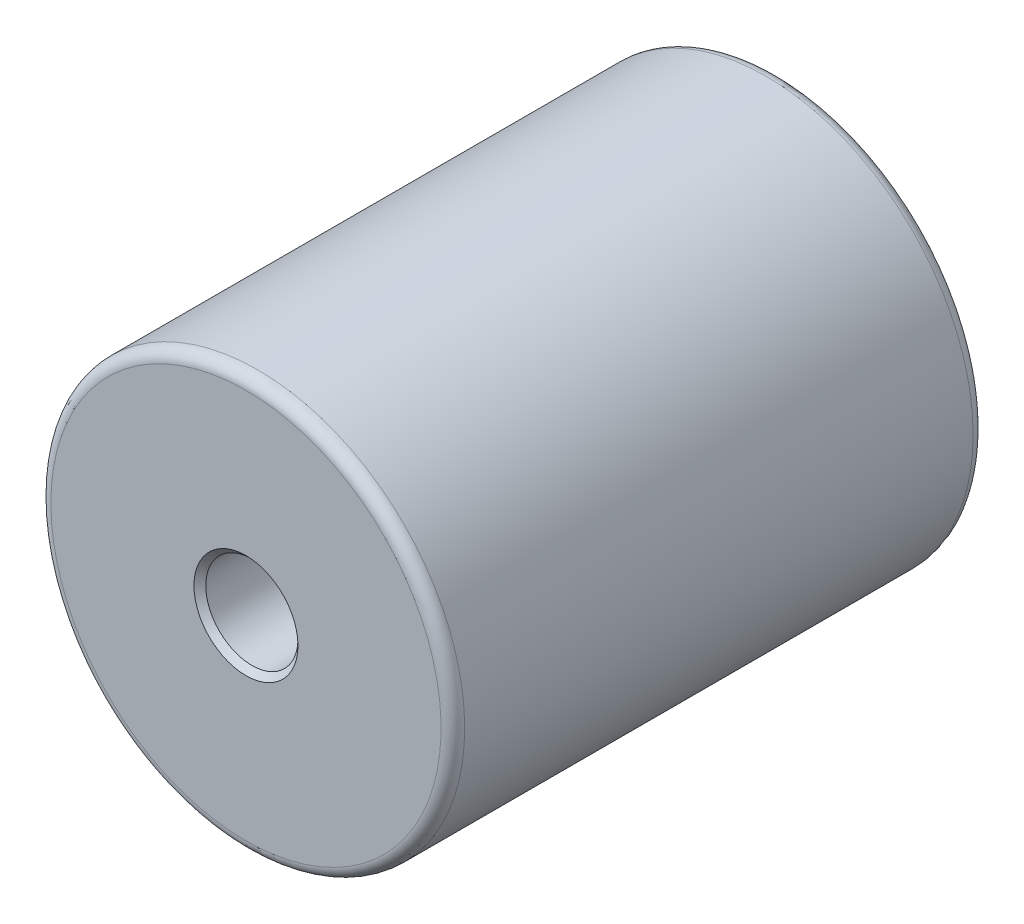
SolidWorks part; units mm, degrees
ref_plane "정면" through (0, 0, 0) normal (0, 0, 1) x (1, 0, 0)
ref_plane "윗면" through (0, 0, 0) normal (0, 1, 0) x (1, 0, 0)
ref_plane "우측면" through (0, 0, 0) normal (1, 0, 0) x (0, 0, -1)
sketch "스케치1" plane through (0, 0, 0) normal (0, 0, 1) x (1, 0, 0)
  line L0 (13.7295, 11.3315) -> (12.2791, 9.2601)
  line L1 (17.5559, 2.9486) -> (15.264, 1.8799)
  line L2 (15.2005, -1.8503) -> (17.4848, -2.9155)
  line L3 (14.0892, 5.9978) -> (16.6, 6.2175)
  line L4 (11.3315, -13.7295) -> (9.2601, -12.2791)
  line L5 (5.9978, -14.0892) -> (6.2175, -16.6)
  line L6 (12.2389, -9.2026) -> (13.6845, -11.2673)
  line L7 (16.6781, -6.2244) -> (14.159, -6.004)
  line L8 (-15.2005, 1.8503) -> (-17.4848, 2.9155)
  line L9 (-17.5559, -2.9486) -> (-15.264, -1.8799)
  line L10 (-16.6781, 6.2244) -> (-14.159, 6.004)
  line L11 (-12.2389, 9.2026) -> (-13.6845, 11.2673)
  line L12 (-14.0892, -5.9978) -> (-16.6, -6.2175)
  line L13 (-13.7295, -11.3315) -> (-12.2791, -9.2601)
  line L14 (-9.2026, -12.2389) -> (-11.2673, -13.6845)
  line L15 (-6.2244, -16.6781) -> (-6.004, -14.159)
  line L16 (-1.8503, -15.2005) -> (-2.9155, -17.4848)
  line L17 (2.9486, -17.5559) -> (1.8799, -15.264)
  line L18 (-5.9978, 14.0892) -> (-6.2175, 16.6)
  line L19 (-11.3315, 13.7295) -> (-9.2601, 12.2791)
  line L20 (9.2026, 12.2389) -> (11.2673, 13.6845)
  line L21 (6.2244, 16.6781) -> (6.004, 14.159)
  line L22 (1.8503, 15.2005) -> (2.9155, 17.4848)
  line L23 (-2.9486, 17.5559) -> (-1.8799, 15.264)
  line L24 (-21, 0) -> (21, 0) construction
  line L25 (0, -21) -> (0, 21) construction
  arc A0 (13.5918, 6.2861) -> (12.2786, 8.5724) centre (0, 0) ccw
  arc A1 (17.8195, -3.5773) -> (17.4848, -2.9155) centre (17.2312, -3.4593) ccw
  arc A2 (15.264, 1.8799) -> (14.9198, 1.2847) centre (15.5176, 1.3361) ccw
  arc A3 (17.5559, 2.9486) -> (17.8352, 3.498) centre (17.3446, 3.4018) ccw
  arc A4 (14.9138, -1.352) -> (15.2005, -1.8503) centre (15.4118, -1.3971) ccw
  arc A5 (14.9138, -1.352) -> (14.9198, 1.2847) centre (0, 0) ccw
  arc A6 (13.5918, 6.2861) -> (14.0892, 5.9978) centre (14.0456, 6.4959) ccw
  arc A7 (9.2601, -12.2791) -> (8.5724, -12.2786) centre (8.9159, -12.7706) ccw
  arc A8 (6.2861, -13.5918) -> (8.5724, -12.2786) centre (0, 0) ccw
  arc A9 (6.2861, -13.5918) -> (5.9978, -14.0892) centre (6.4959, -14.0456) ccw
  arc A10 (11.3315, -13.7295) -> (11.947, -13.6967) centre (11.6183, -13.3199) ccw
  arc A11 (5.8117, -17.2208) -> (6.2175, -16.6) centre (5.6198, -16.6523) ccw
  arc A12 (12.0078, 13.6434) -> (11.2673, 13.6845) centre (11.6114, 13.193) ccw
  arc A13 (13.6434, -12.0078) -> (13.6845, -11.2673) centre (13.193, -11.6114) ccw
  arc A14 (16.6781, -6.2244) -> (17.1947, -5.8882) centre (16.7217, -5.7263) ccw
  arc A15 (14.159, -6.004) -> (13.5632, -6.3474) centre (14.1067, -6.6017) ccw
  arc A16 (12.2398, -8.6278) -> (13.5632, -6.3474) centre (0, 0) ccw
  arc A17 (12.2398, -8.6278) -> (12.2389, -9.2026) centre (12.6484, -8.9159) ccw
  arc A18 (-14.9138, 1.352) -> (-15.2005, 1.8503) centre (-15.4118, 1.3971) ccw
  arc A19 (-14.9138, 1.352) -> (-14.9198, -1.2847) centre (0, 0) ccw
  arc A20 (12.2791, 9.2601) -> (12.2786, 8.5724) centre (12.7706, 8.9159) ccw
  arc A21 (-17.5559, -2.9486) -> (-17.8352, -3.498) centre (-17.3446, -3.4018) ccw
  arc A22 (-16.6781, 6.2244) -> (-17.1947, 5.8882) centre (-16.7217, 5.7263) ccw
  arc A23 (-14.159, 6.004) -> (-13.5632, 6.3474) centre (-14.1067, 6.6017) ccw
  arc A24 (-12.2398, 8.6278) -> (-13.5632, 6.3474) centre (0, 0) ccw
  arc A25 (-12.2398, 8.6278) -> (-12.2389, 9.2026) centre (-12.6484, 8.9159) ccw
  arc A26 (-13.6434, 12.0078) -> (-13.6845, 11.2673) centre (-13.193, 11.6114) ccw
  arc A27 (-17.2208, -5.8117) -> (-16.6, -6.2175) centre (-16.6523, -5.6198) ccw
  arc A28 (17.2208, 5.8117) -> (16.6, 6.2175) centre (16.6523, 5.6198) ccw
  arc A29 (-13.5918, -6.2861) -> (-12.2786, -8.5724) centre (0, 0) ccw
  arc A30 (-12.2791, -9.2601) -> (-12.2786, -8.5724) centre (-12.7706, -8.9159) ccw
  arc A31 (-13.7295, -11.3315) -> (-13.6967, -11.947) centre (-13.3199, -11.6183) ccw
  arc A32 (-13.5918, -6.2861) -> (-14.0892, -5.9978) centre (-14.0456, -6.4959) ccw
  arc A33 (13.7295, 11.3315) -> (13.6967, 11.947) centre (13.3199, 11.6183) ccw
  arc A34 (-12.0078, -13.6434) -> (-11.2673, -13.6845) centre (-11.6114, -13.193) ccw
  arc A35 (-8.6278, -12.2398) -> (-9.2026, -12.2389) centre (-8.9159, -12.6484) ccw
  arc A36 (-8.6278, -12.2398) -> (-6.3474, -13.5632) centre (0, 0) ccw
  arc A37 (-6.004, -14.159) -> (-6.3474, -13.5632) centre (-6.6017, -14.1067) ccw
  arc A38 (-6.2244, -16.6781) -> (-5.8882, -17.1947) centre (-5.7263, -16.7217) ccw
  arc A39 (-3.5773, -17.8195) -> (-2.9155, -17.4848) centre (-3.4593, -17.2312) ccw
  arc A40 (-1.352, -14.9138) -> (-1.8503, -15.2005) centre (-1.3971, -15.4118) ccw
  arc A41 (-1.352, -14.9138) -> (1.2847, -14.9198) centre (0, 0) ccw
  arc A42 (1.8799, -15.264) -> (1.2847, -14.9198) centre (1.3361, -15.5176) ccw
  arc A43 (2.9486, -17.5559) -> (3.498, -17.8352) centre (3.4018, -17.3446) ccw
  arc A44 (-5.8117, 17.2208) -> (-6.2175, 16.6) centre (-5.6198, 16.6523) ccw
  arc A45 (-6.2861, 13.5918) -> (-5.9978, 14.0892) centre (-6.4959, 14.0456) ccw
  arc A46 (-6.2861, 13.5918) -> (-8.5724, 12.2786) centre (0, 0) ccw
  arc A47 (-9.2601, 12.2791) -> (-8.5724, 12.2786) centre (-8.9159, 12.7706) ccw
  arc A48 (-11.3315, 13.7295) -> (-11.947, 13.6967) centre (-11.6183, 13.3199) ccw
  arc A49 (-17.8195, 3.5773) -> (-17.4848, 2.9155) centre (-17.2312, 3.4593) ccw
  arc A50 (-1.8799, 15.264) -> (-1.2847, 14.9198) centre (-1.3361, 15.5176) ccw
  arc A51 (8.6278, 12.2398) -> (9.2026, 12.2389) centre (8.9159, 12.6484) ccw
  arc A52 (8.6278, 12.2398) -> (6.3474, 13.5632) centre (0, 0) ccw
  arc A53 (6.004, 14.159) -> (6.3474, 13.5632) centre (6.6017, 14.1067) ccw
  arc A54 (6.2244, 16.6781) -> (5.8882, 17.1947) centre (5.7263, 16.7217) ccw
  arc A55 (3.5773, 17.8195) -> (2.9155, 17.4848) centre (3.4593, 17.2312) ccw
  arc A56 (-2.9486, 17.5559) -> (-3.498, 17.8352) centre (-3.4018, 17.3446) ccw
  arc A57 (1.352, 14.9138) -> (-1.2847, 14.9198) centre (0, 0) ccw
  arc A58 (1.352, 14.9138) -> (1.8503, 15.2005) centre (1.3971, 15.4118) ccw
  arc A59 (-15.264, -1.8799) -> (-14.9198, -1.2847) centre (-15.5176, -1.3361) ccw
  circle A60 centre (0, 0) radius 18.175
  point P153 (0, 6.5)
  point P154 (0, 6.5)
extrude "보스-돌출1" add sketch "스케치1" along normal mid plane 11 contours A3 A60 A28 L3 A6 A0 A20 L0 A33 A12 L20 A51 A52 A53 L21 A54 A55 L22 A58 A57 A50 L23 A56 A44 L18 A45 A46 A47 L19 A48 A26 L11 A25 A24 A23 L10 A22 A49 L8 A18 A19 A59 L9 A21 A27
sketch "스케치2" plane through (0, 0, 5.5) normal (0, 0, 1) x (1, 0, 0)
  circle A0 centre (0, 0) radius 20
  dimension "D1" = 40
extrude "보스-돌출2" add sketch "스케치2" along normal blind 2
chamfer "모따기1" distance 1.5 angle 50 1 edges at (20, 0, 5.5)
mirror "대칭 복사1" about plane through (0, 0, 0) normal (0, 0, 1) of "모따기1", "보스-돌출2"
sketch "스케치3" plane through (0, 0, -7.5) normal (0, 0, -1) x (-1, 0, 0)
  circle A0 centre (0, 0) radius 3.4
  dimension "D1" = 6.8
extrude "컷-돌출1" cut sketch "스케치3" against normal blind 30
sketch "스케치8" plane through (0, 0, -7.5) normal (0, 0, -1) x (-1, 0, 0)
  circle A0 centre (0, 0) radius 35
  dimension "D1" = 70
extrude "보스-돌출3" add sketch "스케치8" along normal blind 90
sketch "스케치9" plane through (0, 0, 7.5) normal (0, 0, 1) x (1, 0, 0)
  circle A1 centre (0, 0) radius 3.4
  circle A2 centre (0, 0) radius 3.4 construction
extrude "컷-돌출2" cut sketch "스케치9" against normal blind 163
fillet "필렛1" radius 2 2 edges at (-35, 0, -97.5) (-35, 0, -7.5)
sketch "스케치10" plane through (0, 0, 7.5) normal (0, 0, 1) x (1, 0, 0)
  circle A0 centre (0, 0) radius 7.8
  dimension "D1" = 15.6
extrude "컷-돌출3" cut sketch "스케치10" against normal blind 163
chamfer "모따기2" distance 1 angle 45 2 edges at (-7.8, 0, -97.5) (7.8, 0, 7.5)
sketch "스케치11" plane through (0, 0, -7.5) normal (0, 0, 1) x (1, 0, 0)
  circle A0 centre (0, 0) radius 106.7029
extrude "컷-돌출4" cut sketch "스케치11" along normal blind 322
chamfer "모따기3" distance 1 angle 45 1 edges at (7.8, 0, -7.5)
